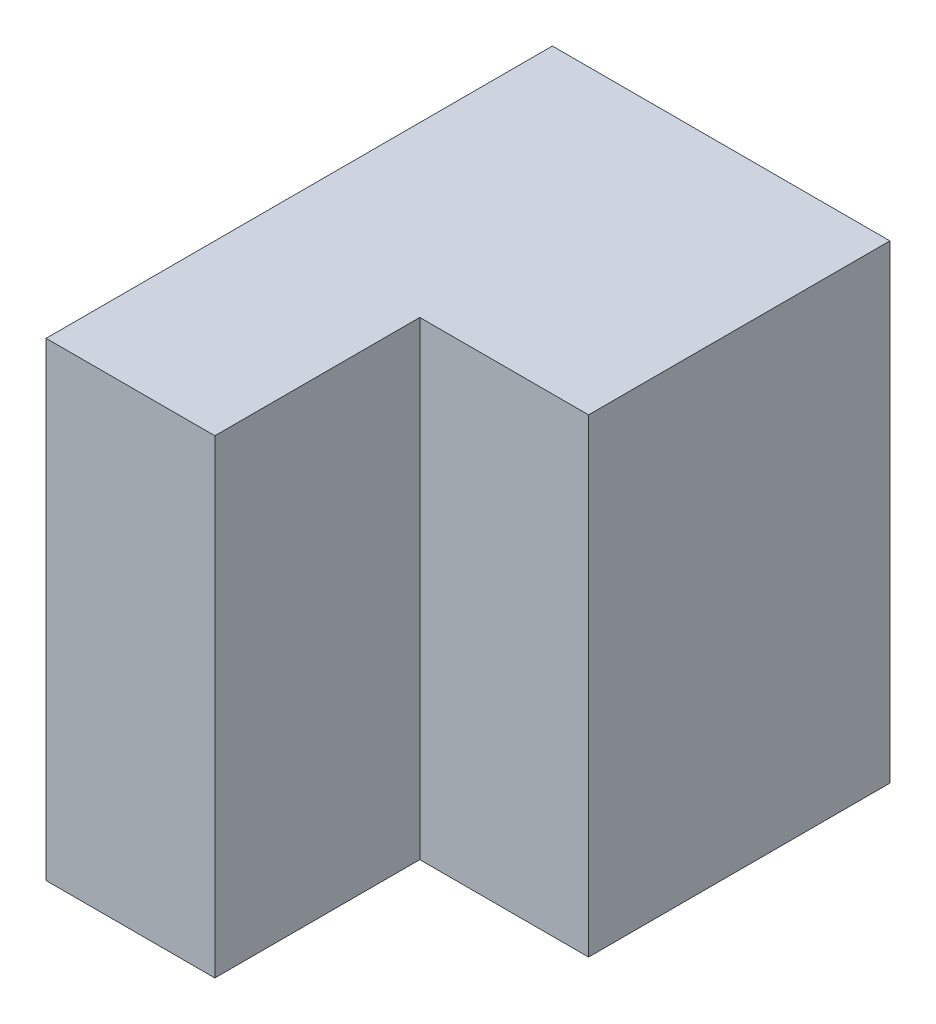
SolidWorks part; units mm, degrees
ref_plane "Front Plane" through (0, 0, 0) normal (0, 0, 1) x (1, 0, 0)
ref_plane "Top Plane" through (0, 0, 0) normal (0, 1, 0) x (1, 0, 0)
ref_plane "Right Plane" through (0, 0, 0) normal (1, 0, 0) x (0, 0, -1)
sketch "Sketch1" plane through (0, 0, 0) normal (1, 0, 0) x (0, 0, -1)
  line L1 (0, 0) -> (15, 0)
  line L2 (0, 0) -> (0, 13.9129)
  line L3 (0, 13.9129) -> (15, 13.9129)
  line L4 (15, 0) -> (15, 13.9129)
  point P5 (15, 0)
  point P6 (15, 13.9129)
  dimension "D1" = 15
extrude "Boss-Extrude1" add sketch "Sketch1" along normal blind 10
sketch "Sketch2" plane through (10, 0, 0) normal (1, 0, 0) x (0, 0, -1)
  line L0 (0, 0) -> (15, 0) construction
  line L1 (0, 13.9129) -> (6.0716, 13.9129)
  line L2 (0, 13.9129) -> (0, 0)
  line L3 (0, 0) -> (6.0716, 0)
  line L4 (6.0716, 13.9129) -> (6.0716, 0)
extrude "Cut-Extrude1" cut sketch "Sketch2" against normal blind 5
